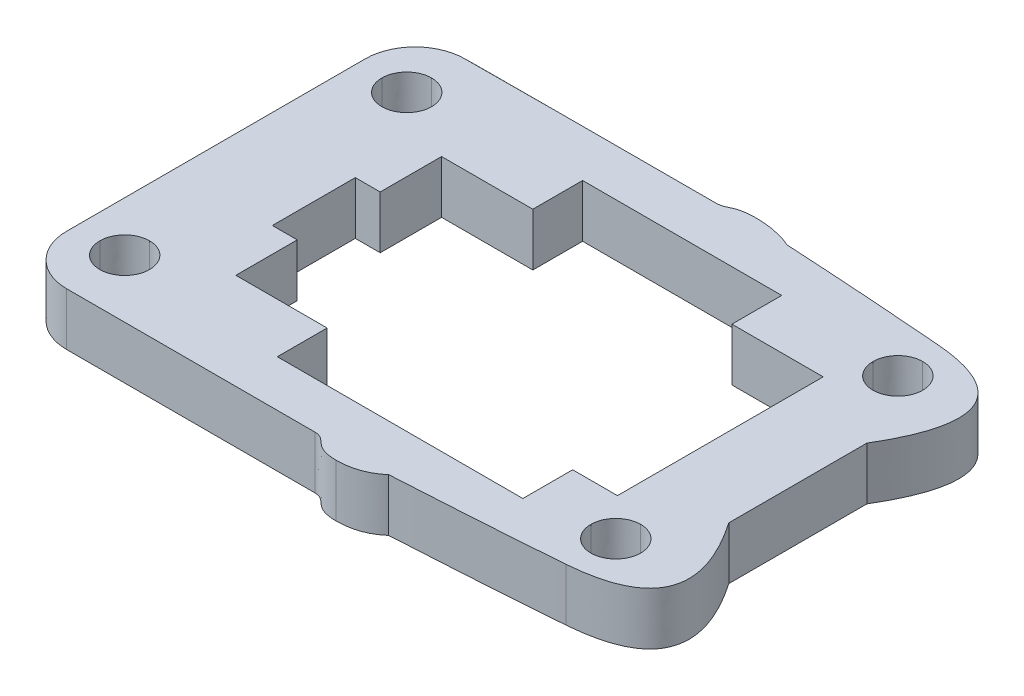
SolidWorks part; units mm, degrees
ref_plane "Front Plane" through (0, 0, 0) normal (0, 0, 1) x (1, 0, 0)
ref_plane "Top Plane" through (0, 0, 0) normal (0, 1, 0) x (1, 0, 0)
ref_plane "Right Plane" through (0, 0, 0) normal (1, 0, 0) x (0, 0, -1)
sketch "Sketch1" plane through (0, 0, 0) normal (0, 1, 0) x (1, 0, 0)
  line L576 (111.51, 9.6305) -> (111.51, 27.6303)
  line L577 (146.6846, 22.6864) -> (146.6846, 14.3671)
  line L578 (117.4101, 16.1303) -> (118.91, 16.1303)
  line L579 (118.91, 16.1303) -> (118.91, 12.4303)
  line L580 (118.91, 12.4303) -> (124.41, 12.4303)
  line L581 (124.41, 12.4303) -> (124.41, 9.4305)
  line L582 (124.41, 9.4305) -> (139.21, 9.4305)
  line L583 (139.21, 9.4305) -> (139.21, 12.4303)
  line L584 (139.21, 12.4303) -> (141.91, 12.4303)
  line L585 (141.91, 12.4303) -> (141.91, 24.8303)
  line L586 (141.91, 24.8303) -> (136.41, 24.8303)
  line L587 (136.41, 24.8303) -> (136.41, 27.8303)
  line L588 (136.41, 27.8303) -> (124.41, 27.8303)
  line L589 (124.41, 27.8303) -> (124.41, 24.8303)
  line L590 (124.41, 24.8303) -> (118.91, 24.8303)
  line L591 (118.91, 24.8303) -> (118.91, 21.1303)
  line L592 (118.91, 21.1303) -> (117.4101, 21.1303)
  line L593 (117.4101, 21.1303) -> (117.4101, 16.1303)
  spline S312 degree 3 poles (116.01, 27.1303) (116.01, 26.3018) (115.3385, 25.6303) (114.5101, 25.6303) knots 0 0 0 0 0.2 0.2 0.2 0.2
  spline S313 degree 3 poles (114.5101, 25.6303) (113.6816, 25.6302) (113.0101, 26.3018) (113.0101, 27.1302) knots 0.2 0.2 0.2 0.2 0.4 0.4 0.4 0.4
  spline S314 degree 3 poles (113.0101, 27.1302) (113.01, 27.9587) (113.6816, 28.6302) (114.51, 28.6303) knots 0.4 0.4 0.4 0.4 0.6 0.6 0.6 0.6
  spline S315 degree 3 poles (114.51, 28.6303) (115.3385, 28.6303) (116.01, 27.9587) (116.01, 27.1303) knots 0.6 0.6 0.6 0.6 1 1 1 1
  spline S316 degree 3 poles (145.61, 10.1305) (145.61, 9.3021) (144.9384, 8.6305) (144.1101, 8.6305) knots 0 0 0 0 0.2 0.2 0.2 0.2
  spline S317 degree 3 poles (144.1101, 8.6305) (143.2817, 8.6305) (142.6101, 9.3021) (142.6101, 10.1304) knots 0.2 0.2 0.2 0.2 0.4 0.4 0.4 0.4
  spline S318 degree 3 poles (142.6101, 10.1304) (142.6101, 10.9588) (143.2817, 11.6302) (144.11, 11.6302) knots 0.4 0.4 0.4 0.4 0.6 0.6 0.6 0.6
  spline S319 degree 3 poles (144.11, 11.6302) (144.9384, 11.6302) (145.61, 10.9588) (145.61, 10.1305) knots 0.6 0.6 0.6 0.6 1 1 1 1
  spline S320 degree 3 poles (116.01, 10.1305) (116.01, 9.3021) (115.3384, 8.6304) (114.5101, 8.6304) knots 0 0 0 0 0.2 0.2 0.2 0.2
  spline S321 degree 3 poles (114.5101, 8.6304) (113.6817, 8.6304) (113.01, 9.3021) (113.01, 10.1304) knots 0.2 0.2 0.2 0.2 0.4 0.4 0.4 0.4
  spline S322 degree 3 poles (113.01, 10.1304) (113.01, 10.9588) (113.6817, 11.6303) (114.51, 11.6303) knots 0.4 0.4 0.4 0.4 0.6 0.6 0.6 0.6
  spline S323 degree 3 poles (114.51, 11.6303) (115.3384, 11.6303) (116.01, 10.9588) (116.01, 10.1305) knots 0.6 0.6 0.6 0.6 1 1 1 1
  spline S324 degree 3 poles (145.61, 27.1303) (145.61, 26.3018) (144.9385, 25.6304) (144.1101, 25.6304) knots 0 0 0 0 0.2 0.2 0.2 0.2
  spline S325 degree 3 poles (144.1101, 25.6304) (143.2816, 25.6303) (142.6102, 26.3018) (142.6102, 27.1302) knots 0.2 0.2 0.2 0.2 0.4 0.4 0.4 0.4
  spline S326 degree 3 poles (142.6102, 27.1302) (142.6101, 27.9587) (143.2816, 28.6301) (144.11, 28.6302) knots 0.4 0.4 0.4 0.4 0.6 0.6 0.6 0.6
  spline S327 degree 3 poles (144.11, 28.6302) (144.9385, 28.6302) (145.61, 27.9587) (145.61, 27.1303) knots 0.6 0.6 0.6 0.6 1 1 1 1
  spline S328 degree 3 poles (111.51, 27.6303) (111.51, 28.4259) (111.8262, 29.189) (112.3888, 29.7516) knots 0.058824 0.058824 0.058824 0.058824 0.117647 0.117647 0.117647 0.117647
  spline S329 degree 3 poles (112.3888, 29.7516) (112.9514, 30.3142) (113.7144, 30.6303) (114.51, 30.6303) knots 0.117647 0.117647 0.117647 0.117647 0.176471 0.176471 0.176471 0.176471
  spline S330 degree 3 poles (114.51, 30.6303) (114.4972, 30.6508) (123.8342, 30.6751) (129.5578, 30.6658) knots 0.176471 0.176471 0.176471 0.176471 0.235294 0.235294 0.235294 0.235294
  spline S331 degree 3 poles (129.5578, 30.6658) (130.305, 30.6646) (130.244, 31.1022) (131.5888, 31.1022) knots 0.235294 0.235294 0.235294 0.235294 0.294118 0.294118 0.294118 0.294118
  spline S332 degree 3 poles (131.5888, 31.1022) (133.0006, 31.1022) (133.901, 30.6448) (133.91, 30.6303) knots 0.294118 0.294118 0.294118 0.294118 0.352941 0.352941 0.352941 0.352941
  spline S333 degree 2 poles (133.91, 30.6303) (138.9519, 30.3475) (143.6753, 29.9652) knots 0.352941 0.352941 0.352941 0.411765 0.411765 0.411765
  spline S334 degree 2 poles (143.6753, 29.9652) (150.7115, 29.3956) (146.6846, 22.6864) knots 0.411765 0.411765 0.411765 0.470588 0.470588 0.470588
  spline S335 degree 2 poles (146.6846, 14.3671) (151.1595, 7.8652) (143.9357, 7.2956) knots 0.529412 0.529412 0.529412 0.588235 0.588235 0.588235
  spline S336 degree 2 poles (143.9357, 7.2956) (139.0863, 6.9133) (133.91, 6.6305) knots 0.588235 0.588235 0.588235 0.647059 0.647059 0.647059
  spline S337 degree 2 poles (133.91, 6.6305) (132.9823, 5.8019) (131.5888, 5.8019) knots 0.647059 0.647059 0.647059 0.705882 0.705882 0.705882
  spline S338 degree 3 poles (131.5888, 5.8019) (130.0782, 5.8019) (130.2699, 6.6305) (129.4696, 6.6305) knots 0.705882 0.705882 0.705882 0.705882 0.764706 0.764706 0.764706 0.764706
  spline S339 degree 2 poles (129.4696, 6.6305) (123.7428, 6.6305) (114.51, 6.6305) knots 0.764706 0.764706 0.764706 0.823529 0.823529 0.823529
  spline S340 degree 3 poles (114.51, 6.6305) (113.7144, 6.6305) (112.9514, 6.9465) (112.3888, 7.5091) knots 0.823529 0.823529 0.823529 0.823529 0.882353 0.882353 0.882353 0.882353
  spline S341 degree 3 poles (112.3888, 7.5091) (111.8262, 8.0717) (111.51, 8.8348) (111.51, 9.6305) knots 0.882353 0.882353 0.882353 0.882353 1 1 1 1
extrude "Boss-Extrude1" add sketch "Sketch1" along normal blind 3.175
